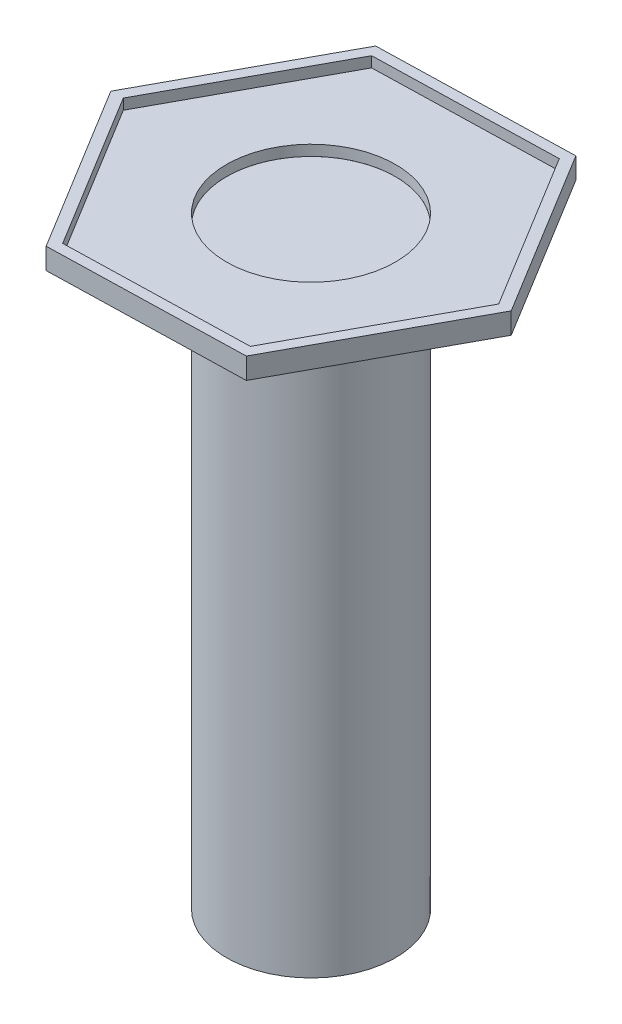
SolidWorks part; units mm, degrees
ref_plane "Front Plane" through (0, 0, 0) normal (0, 0, 1) x (1, 0, 0)
ref_plane "Top Plane" through (0, 0, 0) normal (0, 1, 0) x (1, 0, 0)
ref_plane "Right Plane" through (0, 0, 0) normal (1, 0, 0) x (0, 0, -1)
sketch "Sketch1" plane through (0, 0, 0) normal (0, 1, 0) x (1, 0, 0)
  line L1 (-2.4107, 3.9398) -> (-4.6173, -0.1178)
  line L2 (-4.6173, -0.1178) -> (-2.2066, -4.0576)
  line L3 (-2.2066, -4.0576) -> (2.4107, -3.9398)
  line L4 (2.4107, -3.9398) -> (4.6173, 0.1178)
  line L5 (4.6173, 0.1178) -> (2.2066, 4.0576)
  line L6 (2.2066, 4.0576) -> (-2.4107, 3.9398)
  circle A0 centre (0, 0) radius 4 construction
extrude "Boss-Extrude1" add sketch "Sketch1" along normal blind 0.5
sketch "Sketch2" plane through (0, 0.5, 0) normal (0, 1, 0) x (1, 0, 0)
  line L27 (4.3287, 0.1104) -> (2.0687, 3.804)
  line L28 (2.26, -3.6936) -> (4.3287, 0.1104)
  line L29 (-2.0687, -3.804) -> (2.26, -3.6936)
  line L30 (-4.3287, -0.1104) -> (-2.0687, -3.804)
  line L31 (-2.26, 3.6936) -> (-4.3287, -0.1104)
  line L32 (2.0687, 3.804) -> (-2.26, 3.6936)
  line L33 (4.3287, 0.1104) -> (2.0687, 3.804)
  line L34 (2.26, -3.6936) -> (4.3287, 0.1104)
  line L35 (-2.0687, -3.804) -> (2.26, -3.6936)
  line L36 (-4.3287, -0.1104) -> (-2.0687, -3.804)
  line L37 (-2.26, 3.6936) -> (-4.3287, -0.1104)
  line L38 (2.0687, 3.804) -> (-2.26, 3.6936)
  dimension "D1" = 0.25
extrude "Cut-Extrude1" cut sketch "Sketch2" against normal blind 0.25
sketch "Sketch5" plane through (0, 0.25, 0) normal (0, 1, 0) x (1, 0, 0)
  circle A0 centre (0, 0) radius 2
extrude "Cut-Extrude4" cut sketch "Sketch5" against normal blind 14
sketch "Sketch6" plane through (0, 0, 0) normal (0, -1, 0) x (1, 0, 0)
  circle A0 centre (0, 0) radius 2
extrude "Boss-Extrude3" add sketch "Sketch6" along normal blind 14 separate body
